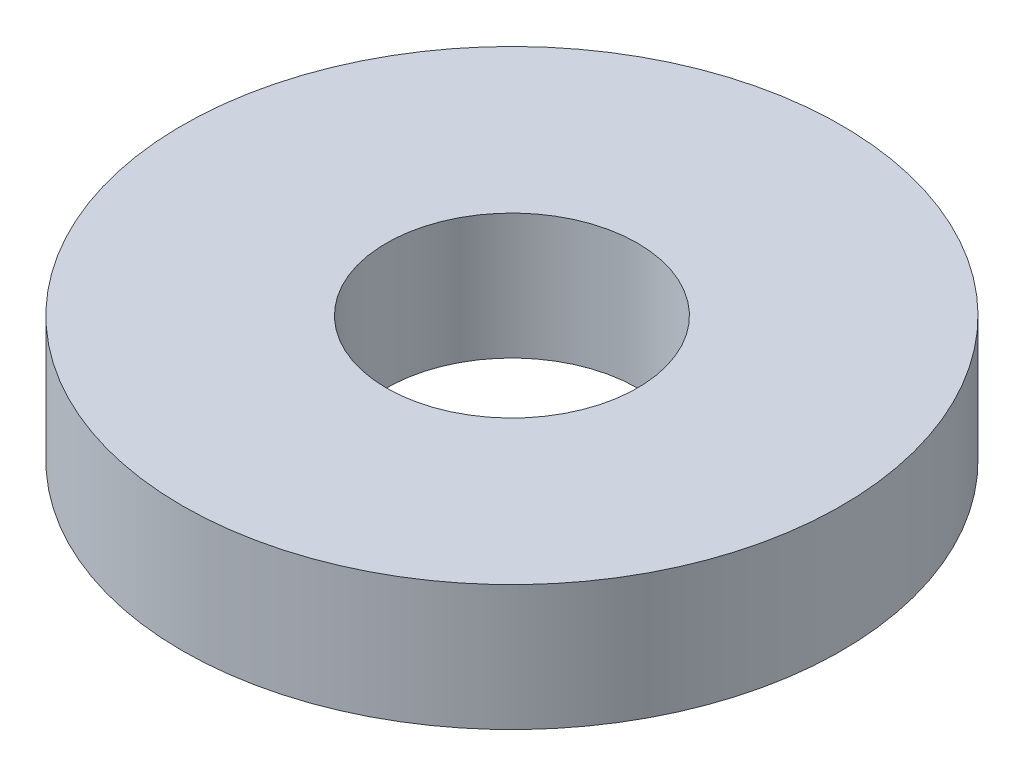
SolidWorks part; units mm, degrees
material "不锈钢 (铁素体)"
ref_plane "前视基准面" through (0, 0, 0) normal (0, 0, 1) x (1, 0, 0)
ref_plane "上视基准面" through (0, 0, 0) normal (0, 1, 0) x (1, 0, 0)
ref_plane "右视基准面" through (0, 0, 0) normal (1, 0, 0) x (0, 0, -1)
sketch "草图1" plane through (0, 0, 0) normal (0, 1, 0) x (1, 0, 0)
  circle A0 centre (0, 0) radius 4
  circle A1 centre (0, 0) radius 10.5
  dimension "D1" = 21
  dimension "D2" = 8
extrude "凸台-拉伸1" add sketch "草图1" along normal blind 4
